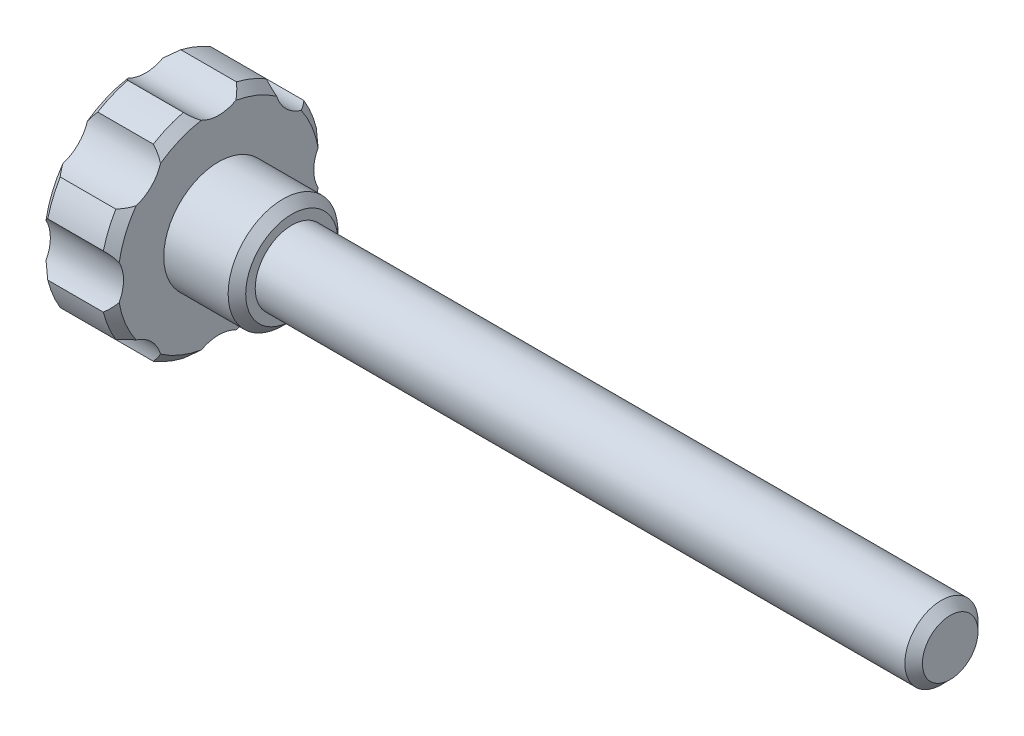
SolidWorks part; units mm, degrees
material "Plain Carbon Steel"
ref_plane "Front Plane" through (0, 0, 0) normal (0, 0, 1) x (1, 0, 0)
ref_plane "Top Plane" through (0, 0, 0) normal (0, 1, 0) x (1, 0, 0)
ref_plane "Right Plane" through (0, 0, 0) normal (1, 0, 0) x (0, 0, -1)
sketch "Sketch1" plane through (0, 0, 0) normal (1, 0, 0) x (0, 0, -1)
  circle A0 centre (0, 0) radius 3.175
  dimension "D1" = 6.35
extrude "Boss-Extrude1" add sketch "Sketch1" along normal blind 57.15
cosmetic thread "Cosmetic Thread1" parameters "D2"=4.8387
chamfer "Chamfer1" distance 0.762 angle 45 1 edges at (57.15, 0, -3.175)
sketch "Sketch6" plane through (0, 0, 0) normal (-1, 0, 0) x (0, 0, 1)
  circle A0 centre (0, 0) radius 4.7625
  dimension "D1" = 9.525
extrude "Boss-Extrude2" add sketch "Sketch6" along normal blind 6.35
sketch "Sketch7" plane through (-6.35, 0, 0) normal (-1, 0, 0) x (0, 0, 1)
  circle A0 centre (0, 0) radius 9.525
  dimension "D1" = 19.05
extrude "Boss-Extrude3" add sketch "Sketch7" along normal blind 6.35
chamfer "Chamfer2" distance 0.762 angle 45 3 edges at (-6.35, 0, 9.525) (-12.7, 0, 9.525) (0, 0, 4.7625)
sketch "Sketch8" plane through (-12.7, 0, 0) normal (-1, 0, 0) x (0, 0, 1)
  circle A0 centre (0, 11.43) radius 3.175
  dimension "D1" = 6.35
  dimension "D2" = 11.43
extrude "Cut-Extrude1" cut sketch "Sketch8" against normal through all
pattern_circular "CirPattern1" count 8 over 360 about axis through (0, 0, 0) along (1, 0, 0) of "Cut-Extrude1"
